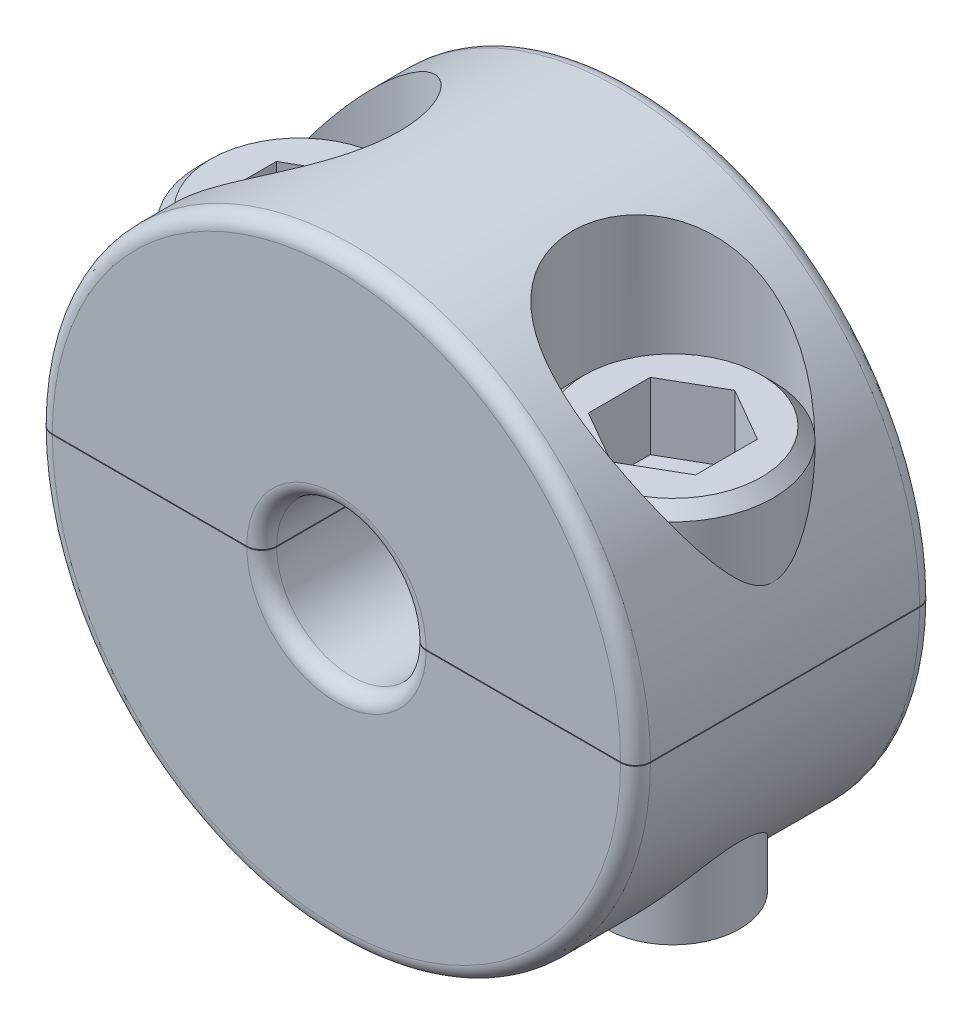
SolidWorks part; units mm, degrees
ref_plane "Front Plane" through (0, 0, 0) normal (0, 0, 1) x (1, 0, 0)
ref_plane "Top Plane" through (0, 0, 0) normal (0, 1, 0) x (1, 0, 0)
ref_plane "Right Plane" through (0, 0, 0) normal (1, 0, 0) x (0, 0, -1)
sketch "Sketch1" plane through (0, 0, 0) normal (0, 0, 1) x (1, 0, 0)
  line L0 (-6.35, 0) -> (-1.5875, 0) construction
  line L1 (-6.35, 0.0079) -> (-1.5875, 0.0079)
  line L2 (-6.35, -0.0079) -> (-1.5875, -0.0079)
  line L3 (1.5875, 0.0079) -> (6.35, 0.0079)
  line L4 (1.5875, -0.0079) -> (6.35, -0.0079)
  line L5 (0, 0) -> (0, 6.35) construction
  circle A0 centre (0, 0) radius 6.35 construction
  circle A1 centre (0, 0) radius 1.5875 construction
  arc A2 (-6.35, 0.0079) -> (6.35, 0.0079) centre (0, 0.0079) cw
  arc A3 (-6.35, -0.0079) -> (6.35, -0.0079) centre (0, -0.0079) ccw
  arc A4 (-1.5875, 0.0079) -> (1.5875, 0.0079) centre (0, 0.0079) cw
  arc A5 (-1.5875, -0.0079) -> (1.5875, -0.0079) centre (0, -0.0079) ccw
  point P4 (6.35, 0)
  dimension "Bore Dia" = 3.175
  dimension "OD" = 12.7
  dimension "Separation" = 0.0159
extrude "Extrude1" add sketch "Sketch1" along normal mid plane 6.35
sketch "Sketch4" plane through (0, 0, 0) normal (0, 0, 1) x (1, 0, 0)
  line L0 (-3.9687, 6.3579) -> (-1.8351, 6.3579)
  line L1 (-1.8351, 6.3579) -> (-1.8351, 0.7191)
  line L2 (-1.8351, 0.7191) -> (-2.5463, 0.7191)
  line L3 (-2.5463, 0.7191) -> (-2.5463, -6.3579)
  line L4 (-2.5463, -6.3579) -> (-3.9687, -6.3579)
  line L5 (-3.9687, -6.3579) -> (-3.9687, 6.3579)
  line L6 (-1.8351, 3.5639) -> (-6.1023, 3.5639) construction
  line L7 (-3.9687, 6.3579) -> (-3.9688, 8.8979) construction
  line L8 (-1.8351, 6.3579) -> (0, 6.3579) construction
  line L9 (0, -6.3579) -> (-2.5463, -6.3579) construction
  line L10 (-6.35, 0) -> (-1.5875, 0) construction
  line L11 (-6.35, 0.0079) -> (-1.5875, 0.0079) construction
  circle A0 centre (0, 0) radius 6.35 construction
  arc A1 (6.35, 0.0079) -> (-6.35, 0.0079) centre (0, 0.0079) ccw construction
  circle A2 centre (0, 0) radius 1.5875 construction
  arc A3 (-6.35, -0.0079) -> (6.35, -0.0079) centre (0, -0.0079) ccw construction
  point P13 (-3.9687, 0)
  point P19 (-3.9687, 0)
  point P20 (-3.9687, 3.5639)
  dimension "D1" = 2.8448
  dimension "D2" = 4.7625
  dimension "D3" = 0.7112
  dimension "D4" = 4.2672
  dimension "D5" = 2.54
  dimension "Screw Dia" = 2.8448
revolve "Cut-Revolve1" cut sketch "Sketch4" angle 360 about L5
sketch "Sketch6" plane through (0, 0, 0) normal (0, 0, 1) x (1, 0, 0)
  line L0 (-3.9687, 3.5639) -> (-1.8351, 3.5639)
  line L1 (-1.8351, 3.5639) -> (-6.1023, 3.5639) construction
  line L2 (-1.8351, 3.5639) -> (-1.8351, 0.7191)
  line L3 (-1.8351, 0.7191) -> (-2.5463, 0.7191)
  line L4 (-2.5463, 0.7191) -> (-2.5463, -4.9705)
  line L5 (-2.5463, 0.7191) -> (-2.5463, -6.3579) construction
  line L6 (-2.5463, -4.9705) -> (-3.9688, -4.9705)
  line L7 (-3.9687, -6.3579) -> (-3.9687, 6.3579) construction
  line L8 (-3.9688, -4.9705) -> (-3.9687, 3.5639)
  line L9 (-2.5463, -4.9705) -> (-5.3911, -4.9705) construction
  dimension "Head Ht" = 2.8448
  dimension "Screw Lg" = 8.5344
revolve "Revolve1" add sketch "Sketch6" angle 360 about L8
mirror "Mirror1" about plane through (0, 0, 0) normal (1, 0, 0) of "Cut-Revolve1"
sketch "Sketch7" plane through (0, 3.5639, 0) normal (0, 1, 0) x (-1, 0, 0)
  line L1 (3.9687, -1.314) -> (5.1067, -0.657)
  line L2 (5.1067, -0.657) -> (5.1067, 0.657)
  line L3 (5.1067, 0.657) -> (3.9687, 1.314)
  line L4 (3.9687, 1.314) -> (2.8308, 0.657)
  line L5 (2.8308, 0.657) -> (2.8308, -0.657)
  line L6 (2.8308, -0.657) -> (3.9687, -1.314)
  circle A0 centre (3.9687, 0) radius 1.1379 construction
  dimension "D1" = 2.2758
extrude "Cut-Extrude2" cut sketch "Sketch7" against normal blind 1.4224
mirror "Mirror2" about plane through (0, 0, 0) normal (1, 0, 0)
fillet "Fillet1" radius 0.3175
fillet "Fillet2" radius 0.3175
chamfer "Chamfer1" distance 0.254 angle 45
chamfer "Chamfer2" distance 0.254 angle 45
equation "\"D1@Sketch4\" = \"Screw Dia@Sketch4\""
equation "\"D4@Sketch4\" = \"Screw Dia@Sketch4\"*1.5"
equation "\"D1@Sketch7\" = \"Screw Dia@Sketch4\"*.8"
equation "\"D1@Cut-Extrude2\" = \"Head Ht@Sketch6\"/2"
equation "\"D3@Sketch4\" = \"D1@Sketch4\"*.25"
equation "\"D1@Fillet1\" = \"Width@Extrude1\"*.05"
equation "\"D1@Fillet2\" = \"D1@Fillet1\""
equation "\"Screw Lg@Sketch6\" = \"Head Ht@Sketch6\"*3"
